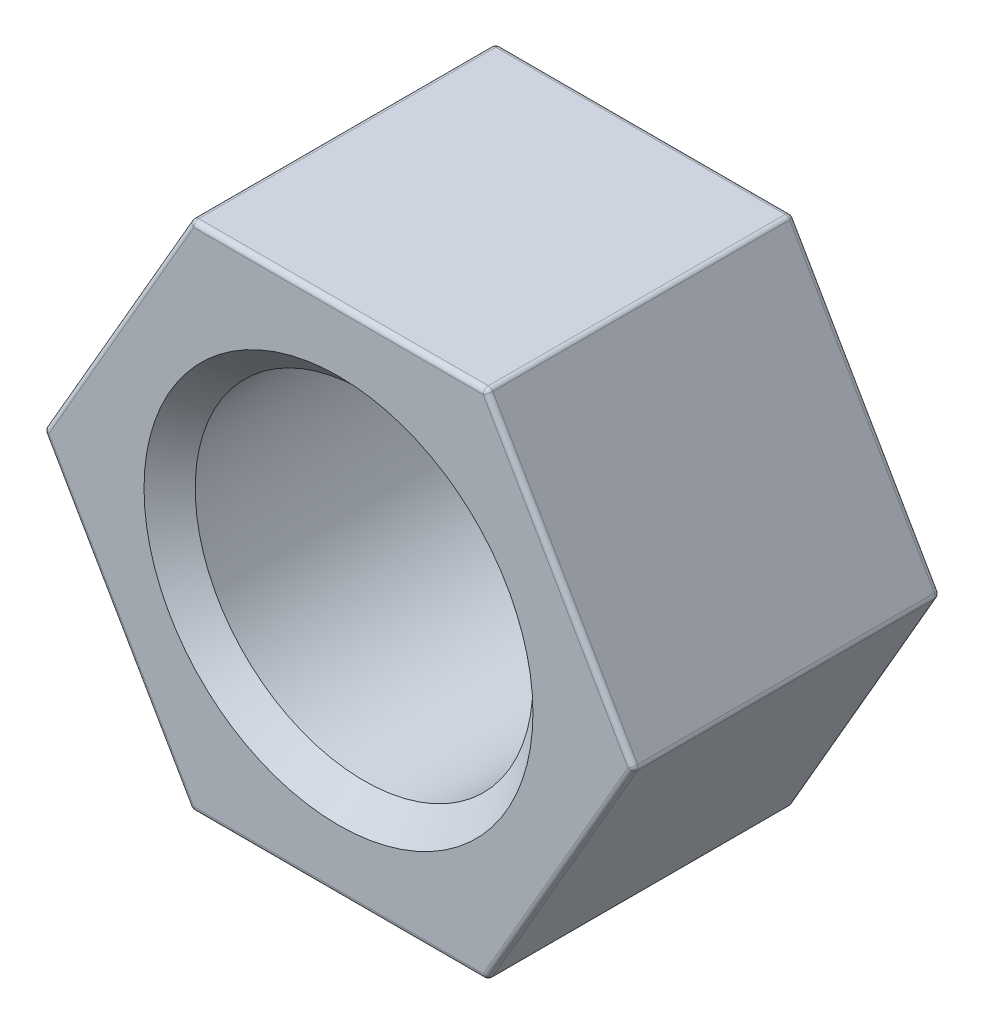
SolidWorks part; units mm, degrees
ref_plane "Front Plane" through (0, 0, 0) normal (0, 0, 1) x (1, 0, 0)
ref_plane "Top Plane" through (0, 0, 0) normal (0, 1, 0) x (1, 0, 0)
ref_plane "Right Plane" through (0, 0, 0) normal (1, 0, 0) x (0, 0, -1)
sketch "Sketch1" plane through (0, 0, 0) normal (0, 0, 1) x (1, 0, 0)
  line L1 (-2.8868, -5) -> (2.8868, -5)
  line L2 (2.8868, -5) -> (5.7735, 0)
  line L3 (5.7735, 0) -> (2.8868, 5)
  line L4 (2.8868, 5) -> (-2.8868, 5)
  line L5 (-2.8868, 5) -> (-5.7735, 0)
  line L6 (-5.7735, 0) -> (-2.8868, -5)
  circle A0 centre (0, 0) radius 5 construction
  circle A1 centre (0, 0) radius 3.3
  dimension "D1" = 10
  dimension "D2" = 6.6
extrude "Boss-Extrude1" add sketch "Sketch1" along normal blind 6
fillet "Fillet1" radius 0.1 18 edges at (-4.3301, 2.5, 6) (-4.3301, 2.5, 0) (-5.7735, 0, 3) (-4.3301, -2.5, 6) (-4.3301, -2.5, 0) (-2.8868, -5, 3) (0, -5, 6) (0, -5, 0) (2.8868, -5, 3) (4.3301, -2.5, 6) (4.3301, -2.5, 0) (5.7735, 0, 3) (4.3301, 2.5, 6) (4.3301, 2.5, 0) (2.8868, 5, 3) (0, 5, 6) (-2.8868, 5, 3) (0, 5, 0)
chamfer "Chamfer1" distance 0.5 angle 45 2 edges at (3.3, 0, 0) (3.3, 0, 6)
